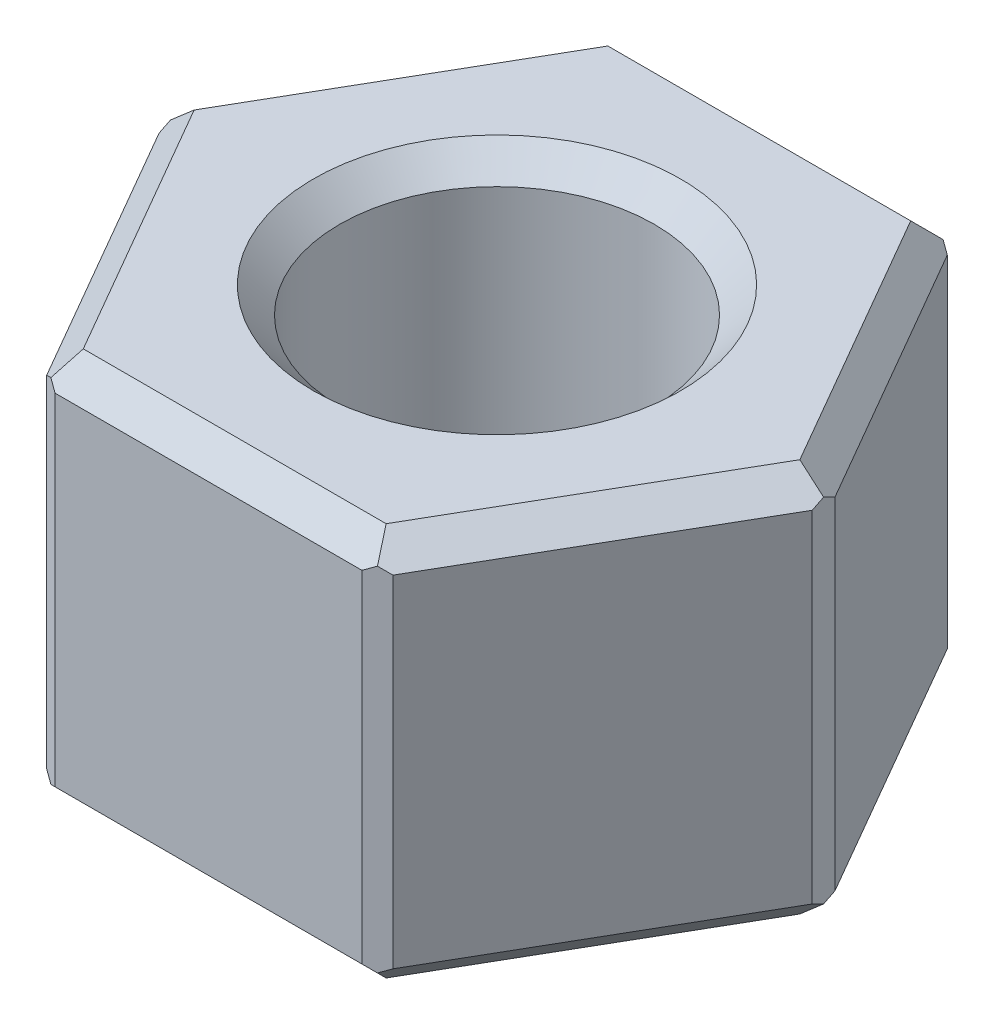
SolidWorks part; units mm, degrees
material "Acciaio al carbonio semplice"
ref_plane "Piano frontale" through (0, 0, 0) normal (0, 0, 1) x (1, 0, 0)
ref_plane "Piano superiore" through (0, 0, 0) normal (0, 1, 0) x (1, 0, 0)
ref_plane "Piano destro" through (0, 0, 0) normal (1, 0, 0) x (0, 0, -1)
sketch "Sketch1" plane through (0, 0, 0) normal (0, 1, 0) x (1, 0, 0)
  line L1 (6.3509, -11) -> (12.7017, 0)
  line L2 (12.7017, 0) -> (6.3509, 11)
  line L3 (6.3509, 11) -> (-6.3509, 11)
  line L4 (-6.3509, 11) -> (-12.7017, 0)
  line L5 (-12.7017, 0) -> (-6.3509, -11)
  line L6 (-6.3509, -11) -> (6.3509, -11)
  circle A0 centre (0, 0) radius 11 construction
  circle A1 centre (0, 0) radius 6
  dimension "D2" = 12
  dimension "D1" = 22
extrude "Extrude1" add sketch "Sketch1" along normal blind 15
cosmetic thread "Filettatura cosmetica1" parameters "D2"=14
chamfer "Smusso2" distance 1 angle 45 14 edges at (0, 0, 6) (9.5263, 0, 5.5) (9.5263, 0, -5.5) (0, 0, -11) (-9.5263, 0, -5.5) (-9.5263, 0, 5.5) (0, 0, 11) (0, 15, 6) (-9.5263, 15, 5.5) (-9.5263, 15, -5.5) (0, 15, -11) (9.5263, 15, -5.5) (9.5263, 15, 5.5) (0, 15, 11)
chamfer "Smusso3" distance 0.5 angle 30 6 edges at (6.3509, 7.5, 11) (12.7017, 7.5, 0) (6.3509, 7.5, -11) (-6.3509, 7.5, -11) (-12.7017, 7.5, 0) (-6.3509, 7.5, 11)
